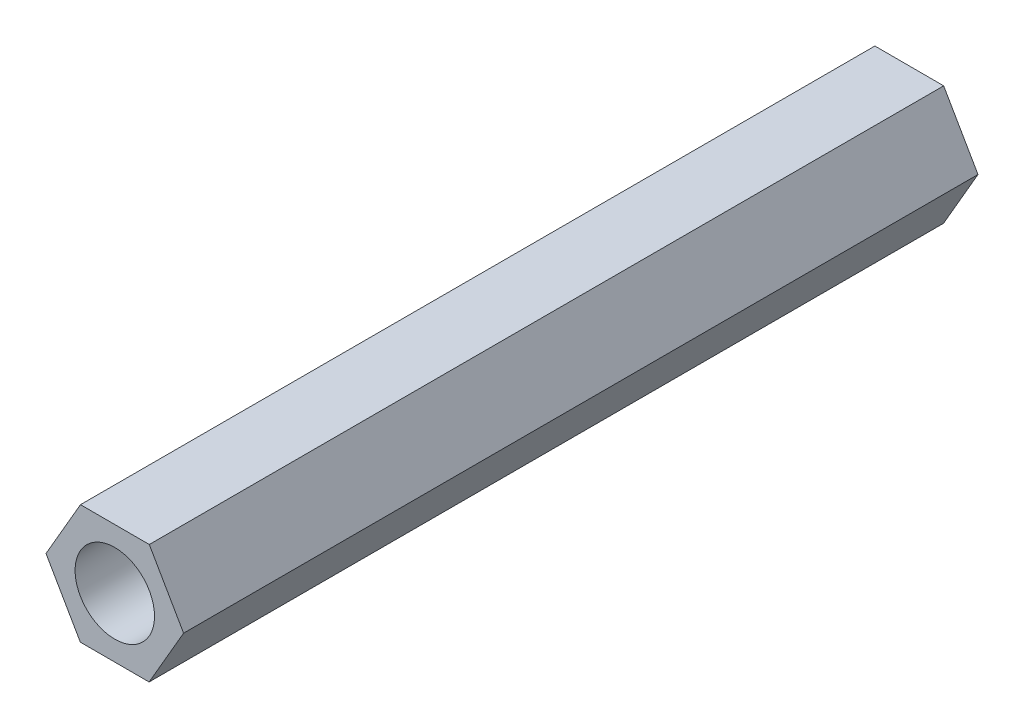
SolidWorks part; units mm, degrees
ref_plane "Front Plane" through (0, 0, 0) normal (0, 0, 1) x (1, 0, 0)
ref_plane "Top Plane" through (0, 0, 0) normal (0, 1, 0) x (1, 0, 0)
ref_plane "Right Plane" through (0, 0, 0) normal (1, 0, 0) x (0, 0, -1)
sketch "Sketch2" plane through (0, 0, 0) normal (0, 0, 1) x (1, 0, 0)
  line L1 (-1.7278, 3.0024) -> (-3.4641, 0.0049)
  line L2 (-3.4641, 0.0049) -> (-1.7363, -2.9975)
  line L3 (-1.7363, -2.9975) -> (1.7278, -3.0024)
  line L4 (1.7278, -3.0024) -> (3.4641, -0.0049)
  line L5 (3.4641, -0.0049) -> (1.7363, 2.9975)
  line L6 (1.7363, 2.9975) -> (-1.7278, 3.0024)
  circle A0 centre (0, 0) radius 3
  circle A1 centre (0, 0) radius 3 construction
  circle A2 centre (0, 0) radius 2
extrude "Boss-Extrude1" add sketch "Sketch2" along normal blind 40 contours A0 A2 | A0 L6 L1 | A0 L5 L6 | A0 L4 L5 | A0 L3 L4 | A0 L2 L3 | A0 L1 L2
